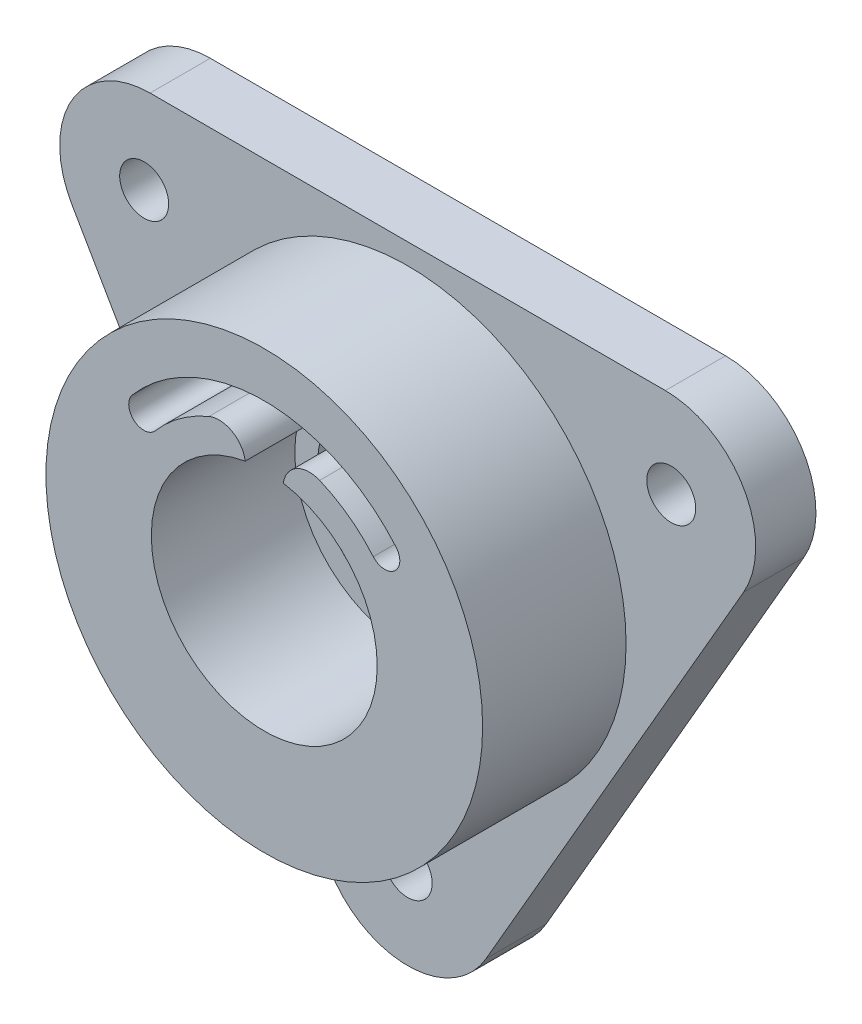
SolidWorks part; units mm, degrees
ref_plane "Plan de face" through (0, 0, 0) normal (0, 0, 1) x (1, 0, 0)
ref_plane "Plan de dessus" through (0, 0, 0) normal (0, 1, 0) x (1, 0, 0)
ref_plane "Plan de droite" through (0, 0, 0) normal (1, 0, 0) x (0, 0, -1)
sketch "Esquisse2" plane through (0, 0, 0) normal (0, 0, 1) x (1, 0, 0)
  circle A0 centre (0, 0) radius 7.5
  circle A1 centre (0, 0) radius 4
  dimension "D1" = 15
  dimension "D2" = 8
sketch "Esquisse1" plane through (0, 0, 0) normal (0, 0, 1) x (1, 0, 0)
  line L0 (-17.5, 10.1036) -> (0, -20.2073) construction
  line L1 (0, -20.2073) -> (17.5, 10.1036) construction
  line L2 (17.5, 10.1036) -> (-17.5, 10.1036) construction
  line L3 (16.0524, 9.2678) -> (-8.4583, -4.8834) construction
  line L4 (0.0575, -0.0332) -> (-30.6383, 17.689) construction
  circle A0 centre (-17.5, 10.1036) radius 1.625
  circle A1 centre (0, -20.2073) radius 1.625
  circle A2 centre (17.5, 10.1036) radius 1.625
  dimension "D2" = 3.25
  dimension "D1" = 35
sketch "Esquisse3" plane through (0, 0, 0) normal (0, 0, 1) x (1, 0, 0)
  line L0 (0, -31.7543) -> (-27.5, 15.8771)
  line L1 (0.0575, -0.0332) -> (-30.6383, 17.689) construction
  line L2 (-27.5, 15.8771) -> (27.5, 15.8771)
  line L3 (16.0524, 9.2678) -> (-8.4583, -4.8834) construction
  line L4 (27.5, 15.8771) -> (0, -31.7543)
  circle A0 centre (-17.5, 10.1036) radius 1.625
  circle A1 centre (17.5, 10.1036) radius 1.625
  circle A2 centre (0, -20.2073) radius 1.625
  circle A3 centre (0, -20.2073) radius 1.625 construction
  circle A4 centre (17.5, 10.1036) radius 1.625 construction
  circle A5 centre (-17.5, 10.1036) radius 1.625 construction
  circle A10 centre (0, 0) radius 6
  circle A13 centre (0, 0) radius 4 construction
  dimension "D2" = 2
  dimension "D1" = 55
extrude "Boss.-Extru.1" add sketch "Esquisse3" along normal blind 4
sketch "Esquisse4" plane through (0, 0, 4) normal (0, 0, 1) x (1, 0, 0)
  circle A3 centre (0, 0) radius 14.5
  circle A4 centre (0, 0) radius 7.5
  circle A5 centre (0, 0) radius 7.5 construction
  dimension "D1" = 7
extrude "Boss.-Extru.2" add sketch "Esquisse4" along normal blind 9.525
fillet "Congé3" radius 6 3 edges at (27.5, 15.8771, 2) (-27.5, 15.8771, 2) (0, -31.7543, 2)
sketch "Esquisse5" plane through (0, 0, 13.525) normal (0, 0, 1) x (1, 0, 0)
  arc A2 (-7.2381, 6.153) -> (7.2381, 6.153) centre (0, 0) cw
  arc A3 (7.2381, 6.153) -> (8.7619, 7.4484) centre (8, 6.8007) ccw
  arc A4 (8.7619, 7.4484) -> (-8.7619, 7.4484) centre (0, 0) ccw
  arc A5 (-8.7619, 7.4484) -> (-7.2381, 6.153) centre (-8, 6.8007) ccw
  circle A6 centre (0, 0) radius 14.5 construction
  circle A7 centre (0, 0) radius 14.5 construction
  circle A8 centre (0, 0) radius 7.5 construction
  point P8 (0, 9.5)
  dimension "D1" = 3
  dimension "D2" = 2
  dimension "D3" = 16
extrude "Enlèv. mat.-Extru.1" cut sketch "Esquisse5" against normal through all
sketch "Esquisse6" plane through (0, 0, 13.525) normal (0, 0, 1) x (1, 0, 0)
  line L0 (-8.0864, 7.1458) -> (8.0864, 7.1458) construction
  arc A0 (-2.3226, 5.5322) -> (-3.6774, 8.7594) centre (-3, 7.1458) ccw
  circle A1 centre (0, 0) radius 6 construction
  arc A2 (7.2381, 6.153) -> (-7.2381, 6.153) centre (0, 0) ccw construction
  arc A3 (3.6774, 8.7594) -> (2.3226, 5.5322) centre (3, 7.1458) ccw
  arc A5 (3.6774, 8.7594) -> (-3.6774, 8.7594) centre (0, 0) ccw
  arc A6 (2.3226, 5.5322) -> (-2.3226, 5.5322) centre (0, 0) ccw
  point P9 (0, 7.1458)
  dimension "D1" = 6
extrude "Enlèv. mat.-Extru.2" cut sketch "Esquisse6" against normal through all
